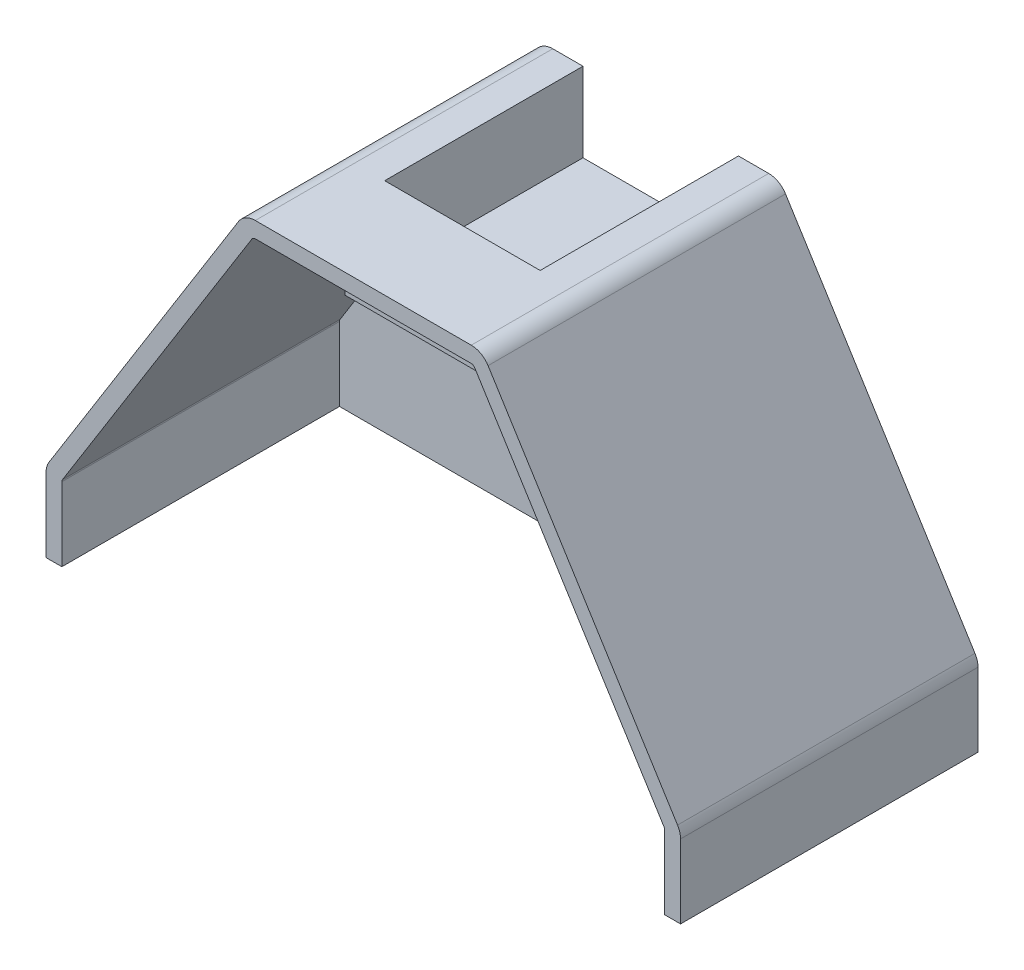
SolidWorks part; units mm, degrees
ref_plane "Front Plane" through (0, 0, 0) normal (0, 0, 1) x (1, 0, 0)
ref_plane "Top Plane" through (0, 0, 0) normal (0, 1, 0) x (1, 0, 0)
ref_plane "Right Plane" through (0, 0, 0) normal (1, 0, 0) x (0, 0, -1)
sketch "Sketch1" plane through (0, 0, 0) normal (0, 0, 1) x (1, 0, 0)
  line L0 (-30, 0) -> (30, 0)
  line L1 (0, 0) -> (0, -100) construction
  line L2 (-80, -100) -> (80, -100)
  line L3 (-80, -100) -> (-80, -80)
  line L4 (80, -100) -> (80, -80)
  line L5 (-30, 0) -> (-80, -80)
  line L6 (30, 0) -> (80, -80)
  dimension "D1" = 60
  dimension "D2" = 30
  dimension "D3" = 100
  dimension "D4" = 160
  dimension "D5" = 80
  dimension "D6" = 20
  dimension "D7" = 20
extrude "Boss-Extrude1" add sketch "Sketch1" along normal blind 5
fillet "Fillet1" radius 5 1 edges at (-30, 0, 2.5)
fillet "Fillet2" radius 5 1 edges at (30, 0, 2.5)
fillet "Fillet3" radius 5 1 edges at (80, -80, 2.5)
fillet "Fillet4" radius 5 1 edges at (-80, -80, 2.5)
sketch "Sketch2" plane through (0, 0, 5) normal (0, 0, 1) x (1, 0, 0)
  line L0 (76, -100) -> (76, -81.434)
  line L1 (75.848, -80.904) -> (28.0768, -4.47)
  line L2 (27.2288, -4) -> (-27.2288, -4)
  line L3 (-28.0768, -4.47) -> (-75.848, -80.904)
  line L4 (-76, -81.434) -> (-76, -100)
  line L5 (-80, -100) -> (-76, -100)
  line L6 (-31.4688, -2.35) -> (-79.24, -78.784)
  line L7 (-80, -81.434) -> (-80, -100)
  line L8 (-80, -100) -> (80, -100)
  line L9 (80, -100) -> (80, -81.434)
  line L10 (79.24, -78.784) -> (31.4688, -2.35)
  line L11 (27.2288, 0) -> (-27.2288, 0)
  line L12 (-31.4688, -2.35) -> (-79.24, -78.784)
  line L13 (-80, -81.434) -> (-80, -100)
  line L15 (80, -100) -> (80, -81.434)
  line L16 (79.24, -78.784) -> (31.4688, -2.35)
  line L17 (27.2288, 0) -> (-27.2288, 0)
  line L18 (76, -100) -> (80, -100)
  arc A0 (76, -81.434) -> (75.848, -80.904) centre (75, -81.434) ccw
  arc A1 (28.0768, -4.47) -> (27.2288, -4) centre (27.2288, -5) ccw
  arc A2 (-27.2288, -4) -> (-28.0768, -4.47) centre (-27.2288, -5) ccw
  arc A3 (-75.848, -80.904) -> (-76, -81.434) centre (-75, -81.434) ccw
  arc A4 (-79.24, -78.784) -> (-80, -81.434) centre (-75, -81.434) ccw
  arc A5 (80, -81.434) -> (79.24, -78.784) centre (75, -81.434) ccw
  arc A6 (31.4688, -2.35) -> (27.2288, 0) centre (27.2288, -5) ccw
  arc A7 (-27.2288, 0) -> (-31.4688, -2.35) centre (-27.2288, -5) ccw
  arc A8 (-79.24, -78.784) -> (-80, -81.434) centre (-75, -81.434) ccw
  arc A9 (80, -81.434) -> (79.24, -78.784) centre (75, -81.434) ccw
  arc A10 (31.4688, -2.35) -> (27.2288, 0) centre (27.2288, -5) ccw
  arc A11 (-27.2288, 0) -> (-31.4688, -2.35) centre (-27.2288, -5) ccw
  dimension "D1" = 0
  dimension "D2" = 4
extrude "Boss-Extrude2" add sketch "Sketch2" along normal blind 70
sketch "Sketch3" plane through (0, 0, 0) normal (0, 0, -1) x (-1, 0, 0)
  line L0 (-27.2288, 0) -> (27.2288, 0) construction
  line L5 (-24.6, 0) -> (-24.6, -25)
  line L6 (-24.6, -25) -> (24.6, -25)
  line L7 (24.6, -25) -> (24.6, 0)
  line L8 (-24.6, 0) -> (24.6, 0)
extrude "Boss-Extrude3" add sketch "Sketch3" against normal blind 55
sketch "Sketch4" plane through (0, 0, 0) normal (0, 1, 0) x (1, 0, 0)
  line L0 (27.2288, 0) -> (-27.2288, 0) construction
  line L1 (-19.6, 0) -> (19.6, 0)
  line L2 (-19.6, 0) -> (-19.6, -50)
  line L3 (-19.6, -50) -> (19.6, -50)
  line L4 (19.6, 0) -> (19.6, -50)
  dimension "D1" = 39.2
  dimension "D2" = 19.6
  dimension "D3" = 50
extrude "Cut-Extrude1" cut sketch "Sketch4" against normal blind 20
